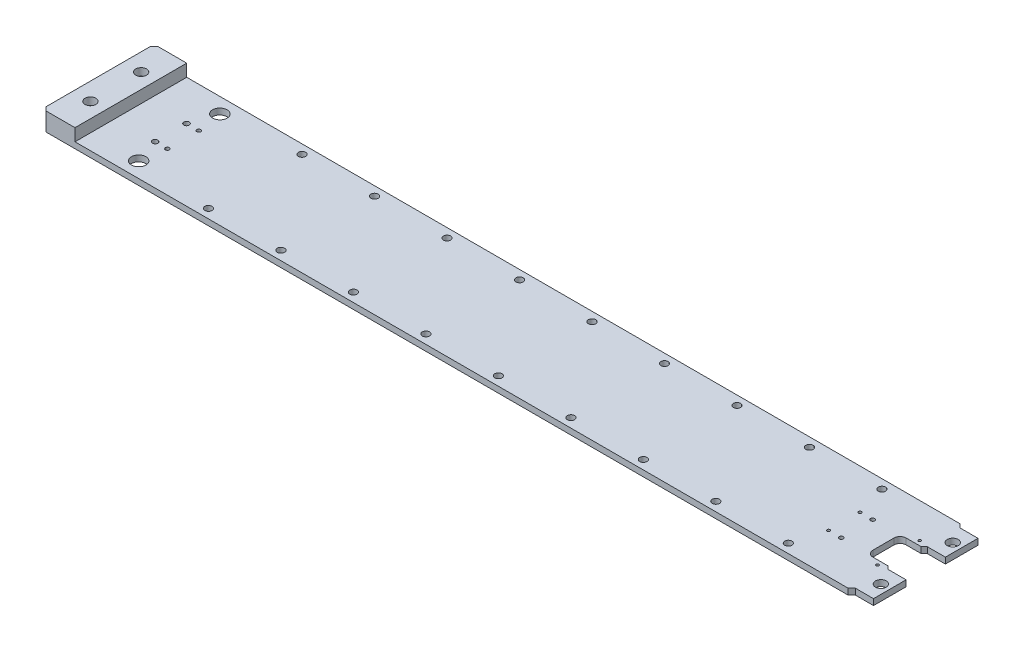
SolidWorks part; units mm, degrees
ref_plane "Front" through (0, 0, 0) normal (0, 0, 1) x (1, 0, 0)
ref_plane "Top" through (0, 0, 0) normal (0, 1, 0) x (1, 0, 0)
ref_plane "Right" through (0, 0, 0) normal (1, 0, 0) x (0, 0, -1)
sketch "Sketch1" plane through (0, 0, 0) normal (0, 1, 0) x (1, 0, 0)
  line L0 (0, 230.4262) -> (0, -124.9674) construction
  line L1 (-286.004, 0) -> (318.4941, 0) construction
  line L2 (326.5, 92.5) -> (-233.5, 92.5)
  line L3 (326.5, 92.5) -> (326.5, -92.5)
  line L4 (326.5, -92.5) -> (-233.5, -92.5)
  line L5 (-233.5, 92.5) -> (-233.5, -92.5)
  dimension "D1" = 560
  dimension "D2" = 185
  dimension "D3" = 233.5
extrude "Boss-Extrude1" add sketch "Sketch1" along normal blind 10
hole_wizard "CBORE for M6 Socket Head Cap Screw1" positions "Sketch3" profile "Sketch2" counterbore size "M6" standard "JIS" end condition through all
sketch "Sketch3" plane through (0, 10, 0) normal (0, 1, 0) x (-1, 0, 0)
  line L2 (-26, 64.5) -> (26, 64.5) construction
  line L3 (-26, 64.5) -> (-26, 44.5) construction
  line L4 (-26, 44.5) -> (26, 44.5) construction
  line L5 (26, 64.5) -> (26, 44.5) construction
  line L11 (0, -230.4262) -> (0, 124.9674) construction
  line L12 (0, -230.4262) -> (0, 124.9674) construction
  line L13 (233.5, 92.5) -> (-326.5, 92.5) construction
  point P1 (26, 44.5)
  point P3 (26, 64.5)
  point P5 (-26, 44.5)
  point P7 (-26, 64.5)
  dimension "D1" = 52
  dimension "D2" = 20
  dimension "D3" = 28
sketch "Sketch2" plane through (-26, 10, 44.5) normal (1, 0, 0) x (0, 0, 1)
  line L0 (0, 0) -> (0, 10)
  line L1 (0, 10) -> (3.3, 10)
  line L3 (3.3, 10) -> (3.3, 6)
  line L4 (3.3, 6) -> (5.5, 6)
  line L5 (5.5, 6) -> (5.5, 0)
  line L7 (5.5, 0) -> (0, 0)
  line L11 (0, -6.35) -> (0, 107.95) construction
  dimension "通し穴の直径" = 6.6
  dimension "通し穴の深さ" = 10
  dimension "座ぐり穴の直径" = 11
  dimension "座ぐり穴の深さ" = 6
sketch "Sketch4" plane through (0, 10, 0) normal (0, 1, 0) x (1, 0, 0)
  line L0 (326.5, 27.5) -> (286.5, 27.5)
  line L1 (326.5, -92.5) -> (326.5, 92.5) construction
  line L2 (286.5, 27.5) -> (286.5, -27.5)
  line L3 (286.5, -27.5) -> (326.5, -27.5)
  line L4 (326.5, -27.5) -> (326.5, 27.5)
  line L5 (151.2603, 0) -> (312.7893, 0) construction
  line L6 (326.5, 92.5) -> (-233.5, 92.5) construction
  line L7 (326.5, -92.5) -> (-233.5, -92.5) construction
  dimension "D1" = 55
  dimension "D2" = 40
extrude "Cut-Extrude1" cut sketch "Sketch4" against normal through all
fillet "Fillet1" radius 10 2 edges at (286.5, 5, 27.5) (286.5, 5, -27.5)
chamfer "Chamfer1" distance 5 angle 45 2 edges at (326.5, 5, 27.5) (326.5, 5, -27.5)
hole_wizard "CBORE for M4 Socket Head Cap Screw1" positions "Sketch7" profile "Sketch6" counterbore size "M4" standard "JIS" end condition through all
sketch "Sketch7" plane through (0, 0, 0) normal (0, -1, 0) x (1, 0, 0)
  line L0 (0, 0) -> (331.4682, 0) construction
  line L2 (326.5, 92.5) -> (326.5, 32.5) construction
  point P0 (311.5, 35)
  point P1 (311.5, -35)
  dimension "D1" = 70
  dimension "D2" = 15
sketch "Sketch6" plane through (311.5, 0, 35) normal (1, 0, 0) x (0, 0, -1)
  line L0 (0, 0) -> (0, 10)
  line L1 (0, 10) -> (2.25, 10)
  line L3 (2.25, 10) -> (2.25, 5)
  line L4 (2.25, 5) -> (4, 5)
  line L5 (4, 5) -> (4, 0)
  line L7 (4, 0) -> (0, 0)
  line L11 (0, -6.35) -> (0, 107.95) construction
  dimension "通し穴の直径" = 4.5
  dimension "通し穴の深さ" = 10
  dimension "座ぐり穴の直径" = 8
  dimension "座ぐり穴の深さ" = 5
hole_wizard "M8x1.25 Tapped Hole1" positions "Sketch9" profile "Sketch8" tap size "M8x1.25" standard "JIS" end condition through all
sketch "Sketch9" plane through (0, 10, 0) normal (0, 1, 0) x (-1, 0, 0)
  line L0 (-326.5, 92.5) -> (-326.5, 32.5) construction
  line L1 (-249.6257, 0) -> (276.0199, 0) construction
  point P0 (-242.5, 26)
  point P1 (-242.5, -26)
  point P7 (162, 26)
  point P9 (162, -26)
  dimension "D1" = 84
  dimension "D2" = 404.5
  dimension "D4" = 52
  dimension "D6" = 52
cosmetic thread "Hole Thread1" parameters "D2"=8
cosmetic thread "Hole Thread2" parameters "D2"=8
cosmetic thread "Hole Thread3" parameters "D2"=8
cosmetic thread "Hole Thread4" parameters "D2"=8
sketch "Sketch8" plane through (242.5, 10, 26) normal (1, 0, 0) x (0, 0, 1)
  line L0 (0, 0) -> (0, 10)
  line L1 (0, 10) -> (3.4, 10)
  line L2 (3.4, 10) -> (3.4, 0)
  line L5 (3.4, 0) -> (0, 0)
  line L11 (0, -6.35) -> (0, 107.95) construction
  dimension "次ｻｰﾌｪｽまでのねじ下穴ﾄﾞﾘﾙ直径" = 6.8
  dimension "次ｻｰﾌｪｽまでのねじ下穴ﾄﾞﾘﾙの深さ" = 10
hole_wizard "M6x1.0 Tapped Hole1" positions "Sketch11" profile "Sketch10" tap size "M6x1.0" standard "JIS"
sketch "Sketch11" plane through (0, 10, 0) normal (0, 1, 0) x (-1, 0, 0)
  line L0 (148.5228, 0) -> (268.4148, 0) construction
  circle A0 centre (162, -26) radius 3.4 construction
  circle A1 centre (-242.5, -26) radius 3.4 construction
  point P0 (143, 26)
  point P1 (143, -26)
  point P16 (-221.5, 26)
  point P18 (-221.5, -26)
  dimension "D1" = 52
  dimension "D2" = 19
  dimension "D3" = 21
sketch "Sketch10" plane through (-143, 10, 26) normal (1, 0, 0) x (0, 0, 1)
  line L0 (0, 0) -> (0, 18.5022)
  line L1 (0, 18.5022) -> (2.5, 17)
  line L2 (2.5, 17) -> (2.5, 0)
  line L5 (2.5, 0) -> (0, 0)
  line L10 (0, 18.5022) -> (-2.5, 17) construction
  line L11 (0, -6.35) -> (0, 107.95) construction
  dimension "ねじ下穴ﾄﾞﾘﾙ直径" = 5
  dimension "ねじ下穴ﾄﾞﾘﾙの深さ" = 17
  dimension "ﾄﾞﾘﾙ角度" = 118
cosmetic thread "Hole Thread7" parameters "D1"=10, "D2"=6
cosmetic thread "Hole Thread8" parameters "D1"=10, "D2"=6
cosmetic thread "Hole Thread11" parameters "D1"=10, "D2"=6
cosmetic thread "Hole Thread12" parameters "D1"=10, "D2"=6
hole_wizard "CBORE for M5 Socket Head Cap Screw1" positions "Sketch15" profile "Sketch14" counterbore size "M5" standard "JIS" end condition through all
sketch "Sketch15" plane through (0, 10, 0) normal (0, 1, 0) x (-1, 0, 0)
  line L0 (-125, 58.0099) -> (-125, 22.6216) construction
  point P0 (-109, 50)
  point P1 (-141, 50)
  dimension "D1" = 32
  dimension "D2" = 50
  dimension "D3" = 125
sketch "Sketch14" plane through (109, 10, 50) normal (1, 0, 0) x (0, 0, 1)
  line L0 (0, 0) -> (0, 10)
  line L1 (0, 10) -> (2.75, 10)
  line L3 (2.75, 10) -> (2.75, 5)
  line L4 (2.75, 5) -> (5, 5)
  line L5 (5, 5) -> (5, 0)
  line L7 (5, 0) -> (0, 0)
  line L11 (0, -6.35) -> (0, 107.95) construction
  dimension "通し穴の直径" = 5.5
  dimension "通し穴の深さ" = 10
  dimension "座ぐり穴の直径" = 10
  dimension "座ぐり穴の深さ" = 5
pattern_linear "Lpattern2" count 2 spacing 250 along (-1, 0, 0) count 2 spacing 100 along (0, 0, -1) of "CBORE for M5 Socket Head Cap Screw1"
ref_plane "Plane1" through (0, 0, 0) normal (-1, 0, 0) x (0, 0, 1)
scale "Scale1" scale about centroid uniform scaling yes scale factor 0.166667
sketch "Sketch17" plane through (-4.7504, 0, 0) normal (-1, 0, 0) x (0, 0, 1)
  line L4 (-15.5446, 4.1604) -> (15.2888, 4.1604)
  line L5 (15.2888, 4.1604) -> (15.2888, 5.8271)
  line L6 (15.2888, 5.8271) -> (-15.5446, 5.8271)
  line L7 (-15.5446, 5.8271) -> (-15.5446, 4.1604)
  line L8 (-15.5446, 4.1604) -> (15.2888, 4.1604)
  line L9 (15.2888, 4.1604) -> (15.2888, 5.8271)
  line L10 (15.2888, 5.8271) -> (-15.5446, 5.8271)
  line L11 (-15.5446, 5.8271) -> (-15.5446, 4.1604)
  dimension "D1" = 0
extrude "Boss-Extrude3" add sketch "Sketch17" along normal blind 130
chamfer "Chamfer2" distance 1 angle 45 4 edges at (-134.7504, 4.9937, -15.5446) (-134.7504, 4.9937, 15.2888) (88.583, 4.9937, 15.2888) (88.583, 4.9937, -15.5446)
sketch "Sketch19" plane through (0, 5.8271, 0) normal (0, 1, 0) x (1, 0, 0)
  circle A3 centre (-114.7236, -4.2052) radius 0.75
  circle A4 centre (-114.7236, 4.4615) radius 0.75
extrude "Cut-Extrude3" cut sketch "Sketch19" against normal up to next
sketch "Sketch20" plane through (0, 5.8271, 0) normal (0, 1, 0) x (1, 0, 0)
  circle A0 centre (-111.3393, 4.4612) radius 0.5417
  circle A1 centre (-111.3393, -4.2054) radius 0.5417
extrude "Cut-Extrude4" cut sketch "Sketch20" against normal up to next
sketch "Sketch22" plane through (0, 5.8271, 0) normal (0, 1, 0) x (1, 0, 0)
  line L0 (-134.7504, -14.2888) -> (-133.7504, -15.2888) construction
  line L1 (-134.7504, -14.2888) -> (-134.7504, 14.5446) construction
  line L2 (-133.7504, 15.5446) -> (-134.7504, 14.5446) construction
  line L3 (-134.7504, -14.2888) -> (-133.7504, -15.2888)
  line L4 (-134.7504, -14.2888) -> (-134.7504, 14.5446)
  line L5 (-133.7504, 15.5446) -> (-134.7504, 14.5446)
  line L6 (-133.7504, -15.2888) -> (87.583, -15.2888) construction
  line L7 (-133.7504, 15.5446) -> (-125.7504, 15.5446)
  line L9 (-133.7504, -15.2888) -> (-125.7504, -15.2888)
  line L10 (-125.7504, 15.5446) -> (-125.7504, -15.2888)
  dimension "D1" = 8
extrude "Boss-Extrude4" add sketch "Sketch22" along normal blind 3.38
sketch "Sketch23" plane through (88.583, 0, 0) normal (1, 0, 0) x (0, 0, -1)
  line L1 (14.5446, 4.1604) -> (5.5446, 4.1604)
  line L2 (14.5446, 4.1604) -> (14.5446, 5.8271)
  line L3 (14.5446, 5.8271) -> (5.5446, 5.8271)
  line L4 (5.5446, 4.1604) -> (5.5446, 5.8271)
  line L5 (-14.2888, 4.1604) -> (-5.2888, 4.1604)
  line L6 (-14.2888, 4.1604) -> (-14.2888, 5.8271)
  line L7 (-14.2888, 5.8271) -> (-5.2888, 5.8271)
  line L8 (-5.2888, 4.1604) -> (-5.2888, 5.8271)
extrude "Boss-Extrude5" add sketch "Sketch23" along normal blind 5
sketch "Sketch24" plane through (0, 5.8271, 0) normal (0, 1, 0) x (1, 0, 0)
  circle A0 centre (91.1097, 10.0448) radius 1.5
  circle A1 centre (91.1097, -9.7885) radius 1.5
extrude "Cut-Extrude5" cut sketch "Sketch24" against normal up to next
sketch "Sketch25" plane through (0, 4.1604, 0) normal (0, -1, 0) x (1, 0, 0)
  circle A0 centre (-129.9089, -7.1282) radius 1.5
  circle A1 centre (-129.9089, 6.8718) radius 1.5
extrude "Cut-Extrude6" cut sketch "Sketch25" against normal up to next
sketch "Sketch26" plane through (0, 4.1604, 0) normal (0, -1, 0) x (1, 0, 0)
  circle A0 centre (-129.9089, -7.1282) radius 2.75
  circle A1 centre (-129.9089, 6.8718) radius 2.75
  dimension "D1" = 5.5
  dimension "D2" = 5.5
extrude "Cut-Extrude7" cut sketch "Sketch26" against normal blind 3
sketch "Sketch27" plane through (0, 5.8271, 0) normal (0, 1, 0) x (1, 0, 0)
  circle A0 centre (15.9996, -8.2054) radius 0.8333 construction
  circle A1 centre (10.6663, -8.2054) radius 0.8333 construction
  circle A2 centre (10.333, -4.2054) radius 0.4167 construction
  circle A3 centre (7.1663, -4.2054) radius 0.5667 construction
  circle A4 centre (7.1663, 4.4612) radius 0.5667 construction
  circle A5 centre (10.333, 4.4612) radius 0.4167 construction
  circle A6 centre (10.6663, 8.4612) radius 0.8333 construction
  circle A7 centre (15.9996, 8.4612) radius 0.8333 construction
  circle A8 centre (15.9996, -8.2054) radius 0.8333
  circle A9 centre (10.6663, -8.2054) radius 0.8333
  circle A10 centre (10.333, -4.2054) radius 0.4167
  circle A11 centre (7.1663, -4.2054) radius 0.5667
  circle A12 centre (7.1663, 4.4612) radius 0.5667
  circle A13 centre (10.333, 4.4612) radius 0.4167
  circle A14 centre (10.6663, 8.4612) radius 0.8333
  circle A15 centre (15.9996, 8.4612) radius 0.8333
extrude "Boss-Extrude7" add sketch "Sketch27" against normal up to surface (1.6667 mm away) up to face at (-129.9089, 4.1604, -9.8782)
sketch "Sketch28" plane through (0, 5.8271, 0) normal (0, 1, 0) x (1, 0, 0)
  circle A0 centre (57.6663, 8.4612) radius 0.8333 construction
  circle A1 centre (52.333, 8.4612) radius 0.8333 construction
  circle A2 centre (57.6663, -8.2054) radius 0.8333 construction
  circle A3 centre (52.333, -8.2054) radius 0.8333 construction
  circle A4 centre (29.833, -7.2888) radius 0.9167 construction
  circle A5 centre (29.833, -10.6221) radius 0.9167 construction
  circle A6 centre (38.4996, -10.6221) radius 0.9167 construction
  circle A7 centre (38.4996, -7.2888) radius 0.9167 construction
  circle A8 centre (57.6663, 8.4612) radius 0.8333
  circle A9 centre (52.333, 8.4612) radius 0.8333
  circle A10 centre (57.6663, -8.2054) radius 0.8333
  circle A11 centre (52.333, -8.2054) radius 0.8333
  circle A12 centre (29.833, -7.2888) radius 0.9167
  circle A13 centre (29.833, -10.6221) radius 0.9167
  circle A14 centre (38.4996, -10.6221) radius 0.9167
  circle A15 centre (38.4996, -7.2888) radius 0.9167
extrude "Boss-Extrude8" add sketch "Sketch28" against normal up to surface (1.6667 mm away) up to face at (-129.9089, 4.1604, -9.8782)
sketch "Sketch29" plane through (0, 5.8271, 0) normal (0, 1, 0) x (1, 0, 0)
  line L0 (-125.7504, -15.2888) -> (87.583, -15.2888) construction
  line L1 (93.583, -5.2888) -> (93.583, -14.2888) construction
  circle A0 centre (68.583, -12.7888) radius 1
  circle A1 centre (48.583, -12.7888) radius 1
  circle A2 centre (28.583, -12.7888) radius 1
  circle A3 centre (8.583, -12.7888) radius 1
  circle A4 centre (-11.417, -12.7888) radius 1
  circle A5 centre (-31.417, -12.7888) radius 1
  circle A6 centre (-51.417, -12.7888) radius 1
  circle A7 centre (-71.417, -12.7888) radius 1
  circle A8 centre (-91.417, -12.7888) radius 1
  circle A9 centre (-111.417, -12.7888) radius 1
  circle A10 centre (68.583, 13.0446) radius 1
  circle A11 centre (48.583, 13.0446) radius 1
  circle A12 centre (28.583, 13.0446) radius 1
  circle A13 centre (8.583, 13.0446) radius 1
  circle A14 centre (-11.417, 13.0446) radius 1
  circle A15 centre (-31.417, 13.0446) radius 1
  circle A16 centre (-51.417, 13.0446) radius 1
  circle A17 centre (-71.417, 13.0446) radius 1
  circle A18 centre (-91.417, 13.0446) radius 1
  circle A19 centre (-111.417, 13.0446) radius 1
  dimension "D1" = 2.5
  dimension "D3" = 25
  dimension "D2" = 10
  dimension "D4" = 10
extrude "Cut-Extrude8" cut sketch "Sketch29" against normal up to next
sketch "Sketch31" plane through (0, 4.1604, 0) normal (0, -1, 0) x (1, 0, 0)
  circle A0 centre (-111.417, 12.7888) radius 1 construction
  circle A1 centre (-111.417, -13.0446) radius 1 construction
  circle A2 centre (-111.417, 12.7888) radius 1
  circle A3 centre (-111.417, -13.0446) radius 1
extrude "Boss-Extrude9" add sketch "Sketch31" against normal up to surface (1.6667 mm away) up to face at (28.583, 5.8271, -14.0446)
sketch "Sketch33" plane through (0, 5.8271, 0) normal (0, 1, 0) x (1, 0, 0)
  circle A0 centre (-112.417, -11.0554) radius 2
  circle A1 centre (-112.417, 11.3446) radius 2
extrude "Cut-Extrude9" cut sketch "Sketch33" against normal up to next
